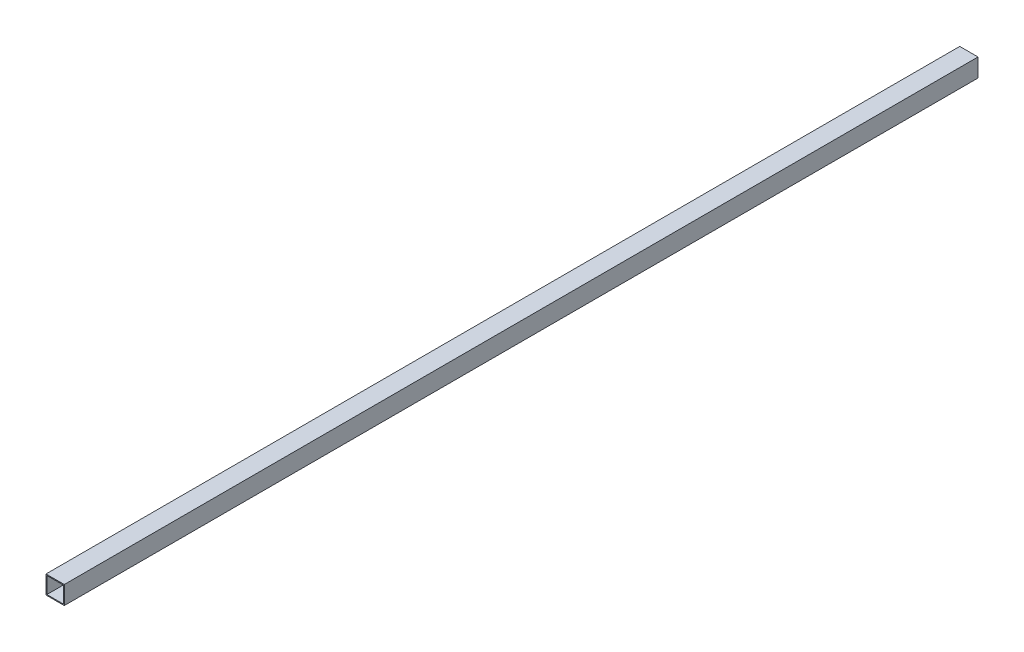
SolidWorks part; units mm, degrees
ref_plane "Front Plane" through (0, 0, 0) normal (0, 0, 1) x (1, 0, 0)
ref_plane "Top Plane" through (0, 0, 0) normal (0, 1, 0) x (1, 0, 0)
ref_plane "Right Plane" through (0, 0, 0) normal (1, 0, 0) x (0, 0, -1)
sketch "Sketch1" plane through (0, 0, 0) normal (0, 0, 1) x (1, 0, 0)
  line L1 (0, 0) -> (20, 0)
  line L2 (0, 0) -> (0, -20)
  line L3 (0, -20) -> (20, -20)
  line L4 (20, 0) -> (20, -20)
  line L5 (1, -19) -> (19, -19)
  line L6 (1, -19) -> (1, -1)
  line L7 (1, -1) -> (19, -1)
  line L8 (19, -19) -> (19, -1)
  line L9 (1, -19) -> (19, -1) construction
  line L10 (1, -1) -> (19, -19) construction
  point P5 (10, -10)
  dimension "D1" = 20
  dimension "D2" = 20
  dimension "D3" = 1
  dimension "D4" = 1
  dimension "D5" = 1
  dimension "D6" = 1
extrude "Boss-Extrude1" add sketch "Sketch1" along normal blind 1000
